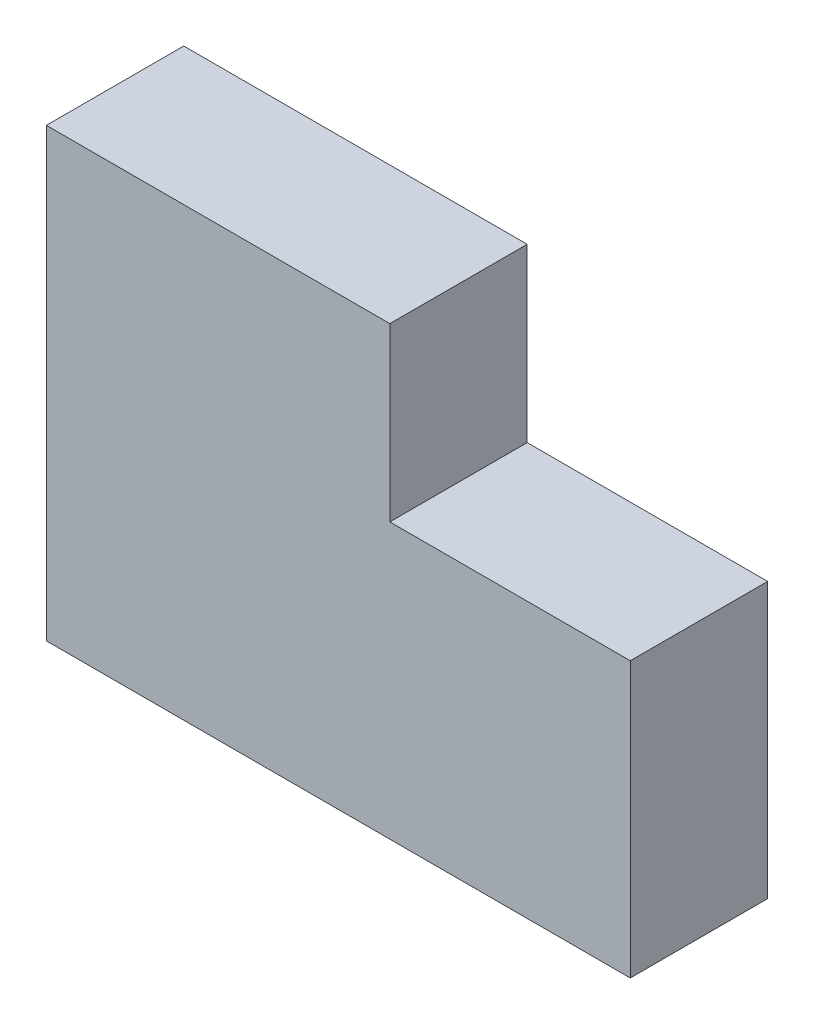
SolidWorks part; units mm, degrees
ref_plane "Plano frontal" through (0, 0, 0) normal (0, 0, 1) x (1, 0, 0)
ref_plane "Plano superior" through (0, 0, 0) normal (0, 1, 0) x (1, 0, 0)
ref_plane "Plano direito" through (0, 0, 0) normal (1, 0, 0) x (0, 0, -1)
sketch "Esboço1" plane through (0, 0, 0) normal (0, 0, 1) x (1, 0, 0)
  line L0 (0, 0) -> (0, 65)
  line L1 (0, 65) -> (50, 65)
  line L2 (50, 65) -> (50, 40)
  line L3 (50, 40) -> (85, 40)
  line L4 (85, 40) -> (85, 0)
  line L5 (85, 0) -> (0, 0)
  dimension "D1" = 85
  dimension "D2" = 65
  dimension "D3" = 50
  dimension "D4" = 40
extrude "Ressalto-extrusão2" add sketch "Esboço1" against normal blind 20
